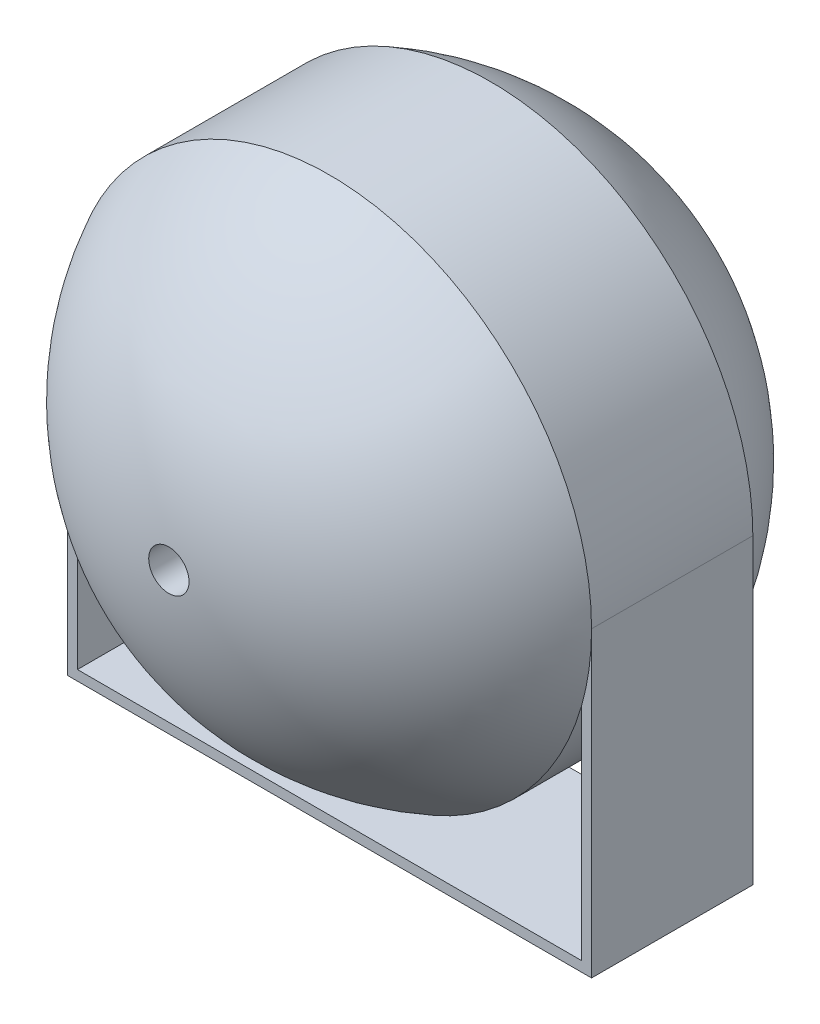
SolidWorks part; units mm, degrees
material "1060 Alloy"
ref_plane "Front Plane" through (0, 0, 0) normal (0, 0, 1) x (1, 0, 0)
ref_plane "Top Plane" through (0, 0, 0) normal (0, 1, 0) x (1, 0, 0)
ref_plane "Right Plane" through (0, 0, 0) normal (1, 0, 0) x (0, 0, -1)
sketch "Sketch1" plane through (0, 0, 0) normal (1, 0, 0) x (0, 0, -1)
  line L0 (0, 0) -> (0, 82.55) construction
  line L5 (25.4, 82.55) -> (-25.4, 82.55)
  line L6 (76.2, 0) -> (-76.2, 0)
  arc A0 (-76.2, 0) -> (-25.4, 82.55) centre (16.2719, 0) cw
  arc A1 (76.2, 0) -> (25.4, 82.55) centre (-16.2719, 0) ccw
  dimension "D1" = 82.55
  dimension "D2" = 25.4
  dimension "D3" = 76.2
revolve "Revolve1" add sketch "Sketch1" angle 360 about L6
sketch "Sketch2" plane through (0, 0, 0) normal (0, 0, 1) x (1, 0, 0)
  circle A0 centre (0, 0) radius 6.35
  dimension "D1" = 12.7
extrude "Cut-Extrude1" cut sketch "Sketch2" against normal through all both and the other way through all
ref_plane "Plane1" through (0, -95.25, 0) normal (0, 1, 0) x (1, 0, 0)
sketch "Sketch3" plane through (0, -95.25, 0) normal (0, 1, 0) x (1, 0, 0)
  line L1 (82.55, -25.4) -> (-82.55, -25.4)
  line L2 (82.55, -25.4) -> (82.55, 25.4)
  line L3 (82.55, 25.4) -> (-82.55, 25.4)
  line L4 (-82.55, -25.4) -> (-82.55, 25.4)
  line L5 (82.55, -25.4) -> (-82.55, 25.4) construction
  line L6 (82.55, 25.4) -> (-82.55, -25.4) construction
  point P0 (0, 0)
extrude "Boss-Extrude1" add sketch "Sketch3" along normal blind 3.175 separate body
sketch "Sketch5" plane through (0, -92.075, 0) normal (0, 1, 0) x (1, 0, 0)
  line L0 (82.55, 25.4) -> (-82.55, 25.4) construction
  line L1 (82.55, -25.4) -> (79.375, -25.4)
  line L2 (82.55, -25.4) -> (82.55, 25.4)
  line L3 (82.55, 25.4) -> (79.375, 25.4)
  line L4 (79.375, -25.4) -> (79.375, 25.4)
  line L5 (0, -25.4) -> (0, 26.3344) construction
  line L6 (-82.55, -25.4) -> (82.55, -25.4) construction
  line L7 (-79.375, -25.4) -> (-79.375, 25.4)
  line L8 (-82.55, 25.4) -> (-79.375, 25.4)
  line L9 (-82.55, -25.4) -> (-82.55, 25.4)
  line L10 (-82.55, -25.4) -> (-79.375, -25.4)
  dimension "D1" = 3.175
extrude "Boss-Extrude2" add sketch "Sketch5" along normal up to next
